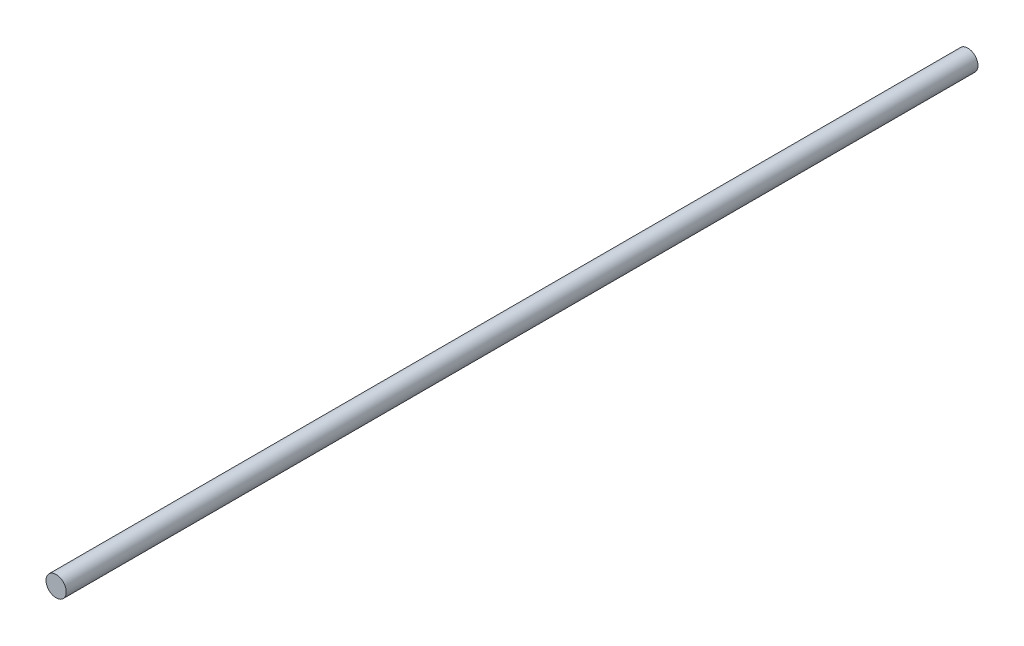
SolidWorks part; units mm, degrees
material "Chrome Stainless Steel"
ref_plane "Front Plane" through (0, 0, 0) normal (0, 0, 1) x (1, 0, 0)
ref_plane "Top Plane" through (0, 0, 0) normal (0, 1, 0) x (1, 0, 0)
ref_plane "Right Plane" through (0, 0, 0) normal (1, 0, 0) x (0, 0, -1)
sketch "Sketch1" plane through (0, 0, 0) normal (0, 0, 1) x (1, 0, 0)
  circle A0 centre (0, 0) radius 2.5
  dimension "D1" = 5
extrude "Boss-Extrude1" add sketch "Sketch1" along normal blind 225
